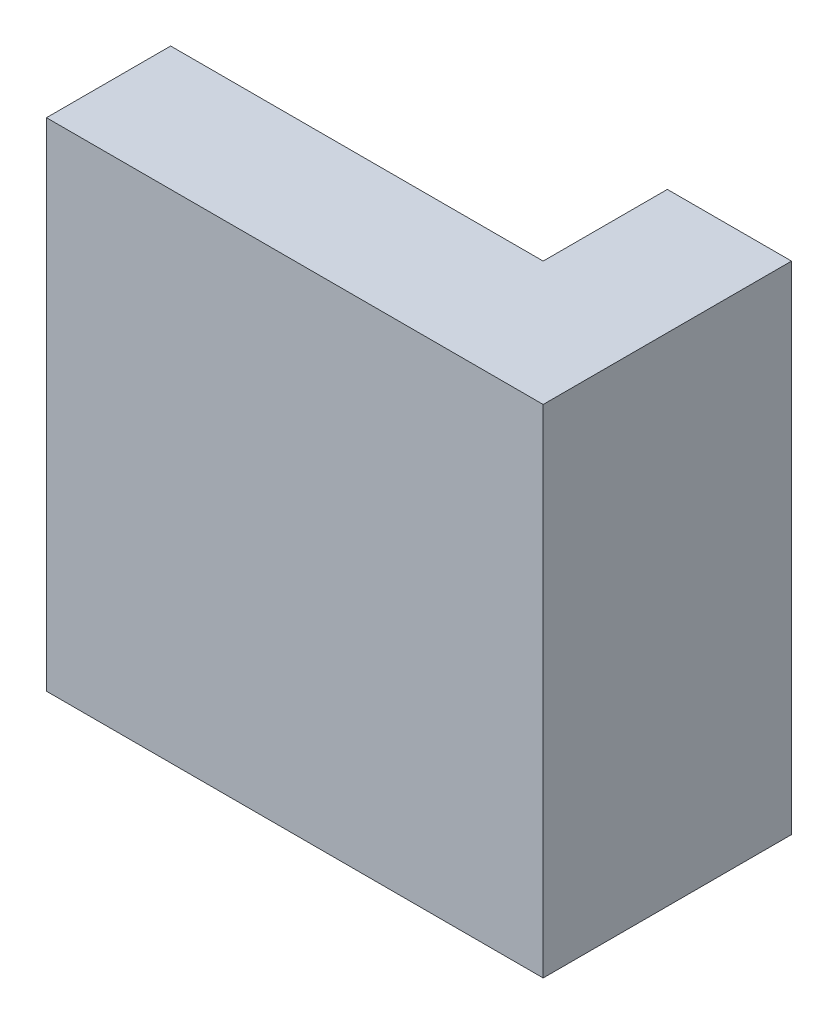
SolidWorks part; units mm, degrees
material "Acrylic (Medium-high impact)"
ref_plane "Front Plane" through (0, 0, 0) normal (0, 0, 1) x (1, 0, 0)
ref_plane "Top Plane" through (0, 0, 0) normal (0, 1, 0) x (1, 0, 0)
ref_plane "Right Plane" through (0, 0, 0) normal (1, 0, 0) x (0, 0, -1)
sketch "Sketch1" plane through (0, 0, 0) normal (0, 1, 0) x (1, 0, 0)
  line L1 (0, 0) -> (12.7, 0)
  line L2 (0, 0) -> (0, 3.175)
  line L3 (0, 3.175) -> (12.7, 3.175)
  line L4 (12.7, 0) -> (12.7, 3.175)
  dimension "D1" = 12.7
  dimension "D2" = 3.175
extrude "Boss-Extrude1" add sketch "Sketch1" along normal blind 12.7
sketch "Sketch2" plane through (0, 0, -3.175) normal (0, 0, -1) x (-1, 0, 0)
  line L5 (-12.7, 0) -> (0, 0) construction
  line L6 (-12.7, 12.7) -> (-9.525, 12.7)
  line L7 (-12.7, 12.7) -> (-12.7, 0)
  line L8 (-12.7, 0) -> (-9.525, 0)
  line L9 (-9.525, 12.7) -> (-9.525, 0)
  dimension "D1" = 3.175
extrude "Boss-Extrude2" add sketch "Sketch2" along normal blind 3.175
